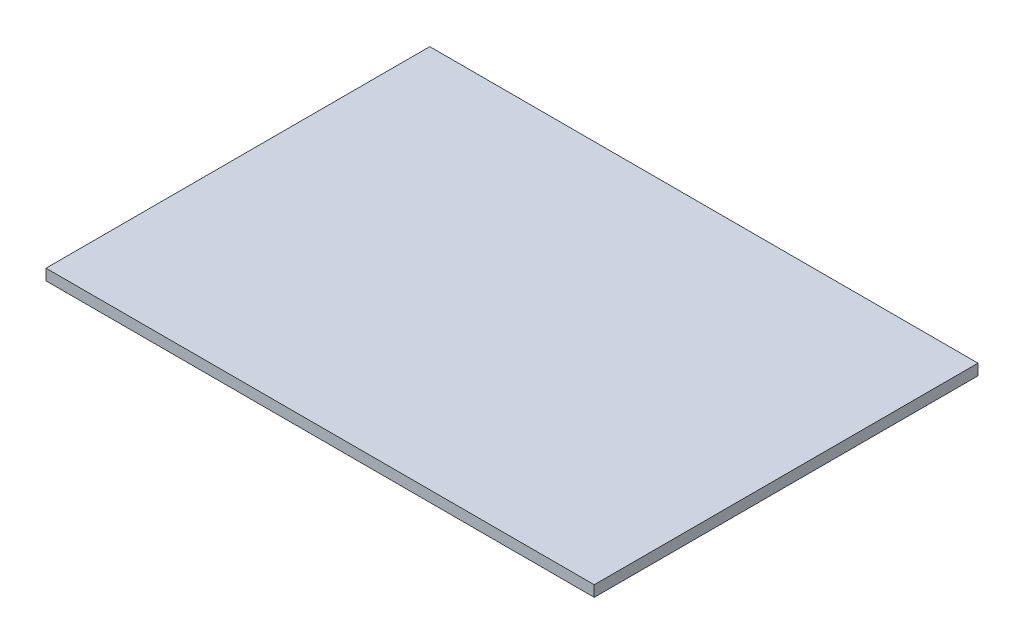
SolidWorks part; units mm, degrees
ref_plane "Front Plane" through (0, 0, 0) normal (0, 0, 1) x (1, 0, 0)
ref_plane "Top Plane" through (0, 0, 0) normal (0, 1, 0) x (1, 0, 0)
ref_plane "Right Plane" through (0, 0, 0) normal (1, 0, 0) x (0, 0, -1)
sketch "Sketch1" plane through (0, 0, 0) normal (0, 1, 0) x (1, 0, 0)
  line L1 (-25, 17.5) -> (25, 17.5)
  line L2 (-25, 17.5) -> (-25, -17.5)
  line L3 (-25, -17.5) -> (25, -17.5)
  line L4 (25, 17.5) -> (25, -17.5)
  line L5 (-25, 17.5) -> (25, -17.5) construction
  line L6 (-25, -17.5) -> (25, 17.5) construction
  point P0 (0, 0)
  dimension "D1" = 50
  dimension "D2" = 35
extrude "Boss-Extrude1" add sketch "Sketch1" along normal blind 1
